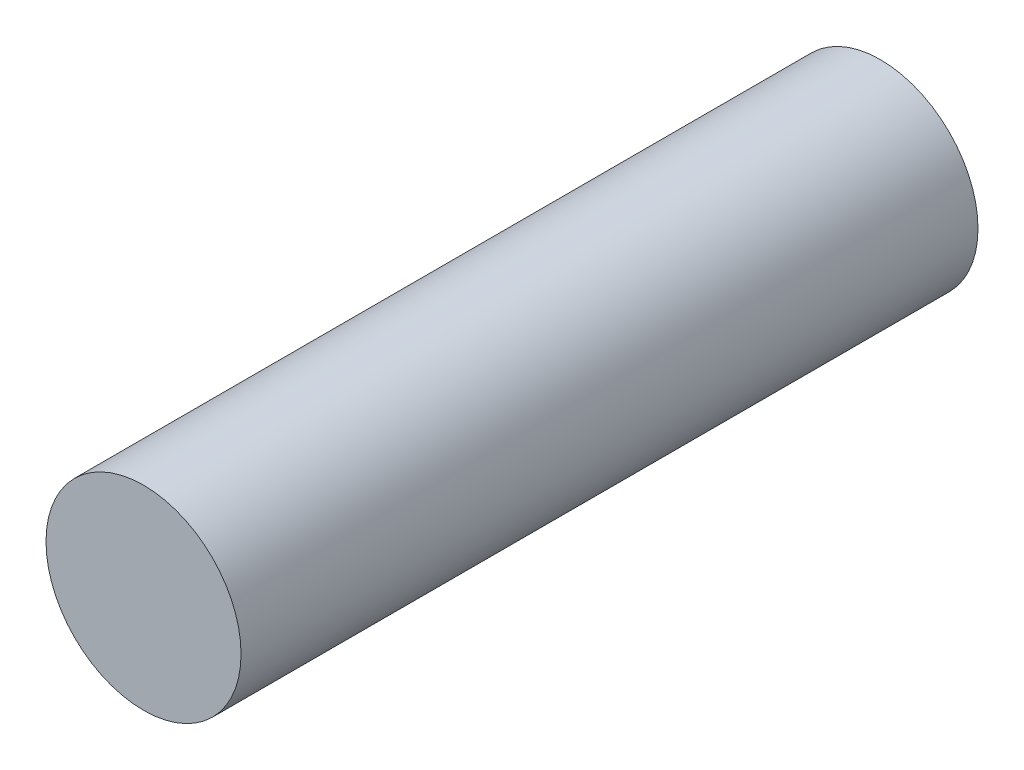
SolidWorks part; units mm, degrees
ref_plane "前视基准面" through (0, 0, 0) normal (0, 0, 1) x (1, 0, 0)
ref_plane "上视基准面" through (0, 0, 0) normal (0, 1, 0) x (1, 0, 0)
ref_plane "右视基准面" through (0, 0, 0) normal (1, 0, 0) x (0, 0, -1)
sketch "草图1" plane through (0, 0, 0) normal (0, 0, 1) x (1, 0, 0)
  circle A0 centre (0, 0) radius 7.94
  dimension "D1" = 15.88
extrude "凸台-拉伸2" add sketch "草图1" along normal blind 60
